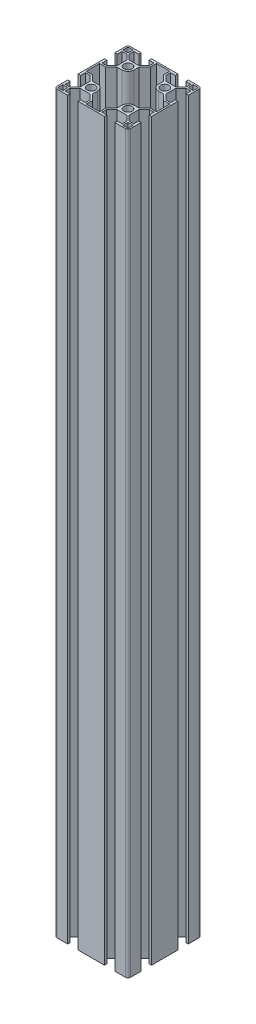
SolidWorks part; units mm, degrees
material "6061 合金"
ref_plane "前视基准面" through (0, 0, 0) normal (0, 0, 1) x (1, 0, 0)
ref_plane "上视基准面" through (0, 0, 0) normal (0, 1, 0) x (1, 0, 0)
ref_plane "右视基准面" through (0, 0, 0) normal (1, 0, 0) x (0, 0, -1)
other "Configuration Table"
sketch "草图1" plane through (0, 0, 0) normal (0, 1, 0) x (1, 0, 0)
  line L0 (-80.888, 0) -> (79.2123, 0) construction
  line L1 (0, 66.3403) -> (0, -67.7113) construction
  line L2 (0, 0) -> (-70.1525, 70.1525) construction
  line L3 (-30, 30) -> (-19.2, 30)
  line L4 (-19.2, 30) -> (-19.2, 28)
  line L5 (-19.2, 28) -> (-23.25, 28)
  line L6 (-23.25, 28) -> (-23.25, 24.1692)
  line L7 (-23.25, 24.1692) -> (-19.0808, 20)
  line L8 (-19.0808, 20) -> (-10.9192, 20)
  line L9 (-10.9192, 20) -> (-6.75, 24.1692)
  line L10 (-6.75, 24.1692) -> (-6.75, 28)
  line L11 (-6.75, 28) -> (-10.8, 28)
  line L12 (-10.8, 28) -> (-10.8, 30)
  line L13 (-10.8, 30) -> (10.8, 30)
  line L14 (-5.45, 28) -> (-5.45, 28.7)
  line L15 (-5.45, 28) -> (-5.45, 23.6308)
  line L16 (-5.45, 23.6308) -> (-10, 19.0808)
  line L17 (-10, 19.0808) -> (-10, 10)
  line L18 (-5.45, 28.7) -> (5.45, 28.7)
  line L19 (-28.7, 28.7) -> (-24.55, 28.7)
  line L20 (-24.55, 28.7) -> (-24.55, 24.55)
  line L21 (-10.9192, 20) -> (-10, 19.0808) construction
  line L22 (-20, 10.9192) -> (-19.0808, 10) construction
  line L23 (-28.7, 24.55) -> (-24.55, 24.55)
  line L24 (-28.7, 28.7) -> (-28.7, 24.55)
  line L25 (-28.7, 5.45) -> (-28.7, -5.45)
  line L26 (-19.0808, 10) -> (-10, 10)
  line L27 (-23.6308, 5.45) -> (-19.0808, 10)
  line L28 (-28, 5.45) -> (-23.6308, 5.45)
  line L29 (-28, 5.45) -> (-28.7, 5.45)
  line L30 (-30, 10.8) -> (-30, -10.8)
  line L31 (-28, 10.8) -> (-30, 10.8)
  line L32 (-28, 6.75) -> (-28, 10.8)
  line L33 (-24.1692, 6.75) -> (-28, 6.75)
  line L34 (-20, 10.9192) -> (-24.1692, 6.75)
  line L35 (-20, 19.0808) -> (-20, 10.9192)
  line L36 (-24.1692, 23.25) -> (-20, 19.0808)
  line L37 (-28, 23.25) -> (-24.1692, 23.25)
  line L38 (-28, 19.2) -> (-28, 23.25)
  line L39 (-30, 19.2) -> (-28, 19.2)
  line L40 (-30, 30) -> (-30, 19.2)
  line L41 (20, 10.9192) -> (19.0808, 10) construction
  line L42 (10.9192, 20) -> (10, 19.0808) construction
  line L43 (0, 0) -> (70.1525, 70.1525) construction
  line L44 (30, 30) -> (30, 19.2)
  line L45 (30, 19.2) -> (28, 19.2)
  line L46 (28, 19.2) -> (28, 23.25)
  line L47 (28, 23.25) -> (24.1692, 23.25)
  line L48 (24.1692, 23.25) -> (20, 19.0808)
  line L49 (20, 19.0808) -> (20, 10.9192)
  line L50 (20, 10.9192) -> (24.1692, 6.75)
  line L51 (24.1692, 6.75) -> (28, 6.75)
  line L52 (28, 6.75) -> (28, 10.8)
  line L53 (28, 10.8) -> (30, 10.8)
  line L54 (30, 10.8) -> (30, -10.8)
  line L55 (28, 5.45) -> (28.7, 5.45)
  line L56 (28, 5.45) -> (23.6308, 5.45)
  line L57 (23.6308, 5.45) -> (19.0808, 10)
  line L58 (19.0808, 10) -> (10, 10)
  line L59 (28.7, 5.45) -> (28.7, -5.45)
  line L60 (28.7, 28.7) -> (28.7, 24.55)
  line L61 (28.7, 24.55) -> (24.55, 24.55)
  line L62 (24.55, 28.7) -> (24.55, 24.55)
  line L63 (28.7, 28.7) -> (24.55, 28.7)
  line L64 (10, 19.0808) -> (10, 10)
  line L65 (5.45, 23.6308) -> (10, 19.0808)
  line L66 (5.45, 28) -> (5.45, 23.6308)
  line L67 (5.45, 28) -> (5.45, 28.7)
  line L68 (10.8, 28) -> (10.8, 30)
  line L69 (6.75, 28) -> (10.8, 28)
  line L70 (6.75, 24.1692) -> (6.75, 28)
  line L71 (10.9192, 20) -> (6.75, 24.1692)
  line L72 (19.0808, 20) -> (10.9192, 20)
  line L73 (23.25, 24.1692) -> (19.0808, 20)
  line L74 (23.25, 28) -> (23.25, 24.1692)
  line L75 (19.2, 28) -> (23.25, 28)
  line L76 (19.2, 30) -> (19.2, 28)
  line L77 (30, 30) -> (19.2, 30)
  line L78 (0, 0) -> (70.1525, -70.1525) construction
  line L79 (10.9192, -20) -> (10, -19.0808) construction
  line L80 (20, -10.9192) -> (19.0808, -10) construction
  line L81 (-20, -10.9192) -> (-19.0808, -10) construction
  line L82 (-10.9192, -20) -> (-10, -19.0808) construction
  line L83 (0, 0) -> (-70.1525, -70.1525) construction
  line L84 (30, -30) -> (19.2, -30)
  line L85 (19.2, -30) -> (19.2, -28)
  line L86 (19.2, -28) -> (23.25, -28)
  line L87 (23.25, -28) -> (23.25, -24.1692)
  line L88 (23.25, -24.1692) -> (19.0808, -20)
  line L89 (19.0808, -20) -> (10.9192, -20)
  line L90 (10.9192, -20) -> (6.75, -24.1692)
  line L91 (6.75, -24.1692) -> (6.75, -28)
  line L92 (6.75, -28) -> (10.8, -28)
  line L93 (10.8, -28) -> (10.8, -30)
  line L94 (5.45, -28) -> (5.45, -28.7)
  line L95 (5.45, -28) -> (5.45, -23.6308)
  line L96 (5.45, -23.6308) -> (10, -19.0808)
  line L97 (10, -19.0808) -> (10, -10)
  line L98 (28.7, -28.7) -> (24.55, -28.7)
  line L99 (24.55, -28.7) -> (24.55, -24.55)
  line L100 (28.7, -24.55) -> (24.55, -24.55)
  line L101 (28.7, -28.7) -> (28.7, -24.55)
  line L102 (19.0808, -10) -> (10, -10)
  line L103 (23.6308, -5.45) -> (19.0808, -10)
  line L104 (28, -5.45) -> (23.6308, -5.45)
  line L105 (28, -5.45) -> (28.7, -5.45)
  line L106 (28, -10.8) -> (30, -10.8)
  line L107 (28, -6.75) -> (28, -10.8)
  line L108 (24.1692, -6.75) -> (28, -6.75)
  line L109 (20, -10.9192) -> (24.1692, -6.75)
  line L110 (20, -19.0808) -> (20, -10.9192)
  line L111 (24.1692, -23.25) -> (20, -19.0808)
  line L112 (28, -23.25) -> (24.1692, -23.25)
  line L113 (28, -19.2) -> (28, -23.25)
  line L114 (30, -19.2) -> (28, -19.2)
  line L115 (30, -30) -> (30, -19.2)
  line L116 (-30, -30) -> (-30, -19.2)
  line L117 (-30, -19.2) -> (-28, -19.2)
  line L118 (-28, -19.2) -> (-28, -23.25)
  line L119 (-28, -23.25) -> (-24.1692, -23.25)
  line L120 (-24.1692, -23.25) -> (-20, -19.0808)
  line L121 (-20, -19.0808) -> (-20, -10.9192)
  line L122 (-20, -10.9192) -> (-24.1692, -6.75)
  line L123 (-24.1692, -6.75) -> (-28, -6.75)
  line L124 (-28, -6.75) -> (-28, -10.8)
  line L125 (-28, -10.8) -> (-30, -10.8)
  line L126 (-28, -5.45) -> (-28.7, -5.45)
  line L127 (-28, -5.45) -> (-23.6308, -5.45)
  line L128 (-23.6308, -5.45) -> (-19.0808, -10)
  line L129 (-19.0808, -10) -> (-10, -10)
  line L130 (-28.7, -28.7) -> (-28.7, -24.55)
  line L131 (-28.7, -24.55) -> (-24.55, -24.55)
  line L132 (-24.55, -28.7) -> (-24.55, -24.55)
  line L133 (-28.7, -28.7) -> (-24.55, -28.7)
  line L134 (-5.45, -28.7) -> (5.45, -28.7)
  line L135 (-10, -19.0808) -> (-10, -10)
  line L136 (-5.45, -23.6308) -> (-10, -19.0808)
  line L137 (-5.45, -28) -> (-5.45, -23.6308)
  line L138 (-5.45, -28) -> (-5.45, -28.7)
  line L139 (-10.8, -30) -> (10.8, -30)
  line L140 (-10.8, -28) -> (-10.8, -30)
  line L141 (-6.75, -28) -> (-10.8, -28)
  line L142 (-6.75, -24.1692) -> (-6.75, -28)
  line L143 (-10.9192, -20) -> (-6.75, -24.1692)
  line L144 (-19.0808, -20) -> (-10.9192, -20)
  line L145 (-23.25, -24.1692) -> (-19.0808, -20)
  line L146 (-23.25, -28) -> (-23.25, -24.1692)
  line L147 (-19.2, -28) -> (-23.25, -28)
  line L148 (-19.2, -30) -> (-19.2, -28)
  line L149 (-30, -30) -> (-19.2, -30)
  circle A0 centre (-15, 15) radius 3.4
  circle A1 centre (15, 15) radius 3.4
  circle A2 centre (15, -15) radius 3.4
  circle A3 centre (-15, -15) radius 3.4
  point P75 (0, 28.7)
  point P78 (0, 30)
  point P119 (28.7, 0)
  point P122 (30, 0)
  point P140 (-30, 0)
  point P144 (-28.7, 0)
  point P160 (0, -30)
  point P161 (0, -28.7)
  dimension "D14" = 6.8
  dimension "D2" = 30
  dimension "D3" = 8.4
  dimension "D4" = 10.8
  dimension "D5" = 2
  dimension "D6" = 2
  dimension "D7" = 16.5
  dimension "D8" = 1.3
  dimension "D9" = 1.3
  dimension "D10" = 4.05
  dimension "D11" = 1.3
  dimension "D12" = 10
  dimension "D13" = 1.3
  dimension "D15" = 1.3
  dimension "D16" = 1.3
  dimension "D17" = 15
extrude "凸台-拉伸1" add sketch "草图1" along normal blind 600 contours L137 L138 L134 L94 L95 L96 L97 L102 L103 L104 L105 L59 L55 L56 L57 L58 L64 L65 L66 L67 L18 L14 L15 L16 L17 L26 L27 L28 L29 L25 L126 L127 L128 L129 L135 L136 | A2 | A1 | A0 | A3 | L98 L101 L100 L99 | L60 L63 L62 L61 | L19 L24 L23 L20 | L130 L133 L132 L131 | L44 L45 L46 L47 L48 L49 L50 L51 L52 L53 L54 L106 L107 L108 L109 L110 L111 L112 L113 L114 L115 L84 L85 L86 L87 L88 L89 L90 L91 L92 L93 L139 L140 L141 L142 L143 L144 L145 L146 L147 L148 L149 L116 L117 L118 L119 L120 L121 L122 L123 L124 L125 L30 L31 L32 L33 L34 L35 L36 L37 L38 L39 L40 L3 L4 L5 L6 L7 L8 L9 L10 L11 L12 L13 L68 L69 L70 L71 L72 L73 L74 L75 L76 L77
fillet "圆角1" radius 0.7 4 edges at (-28.7, 300, 28.7) (-28.7, 300, -28.7) (28.7, 300, -28.7) (28.7, 300, 28.7)
fillet "圆角2" radius 2 4 edges at (30, 300, 30) (-30, 300, 30) (-30, 300, -30) (30, 300, -30)
fillet "圆角3" radius 5 4 edges at (10, 300, 10) (10, 300, -10) (-10, 300, -10) (-10, 300, 10)
